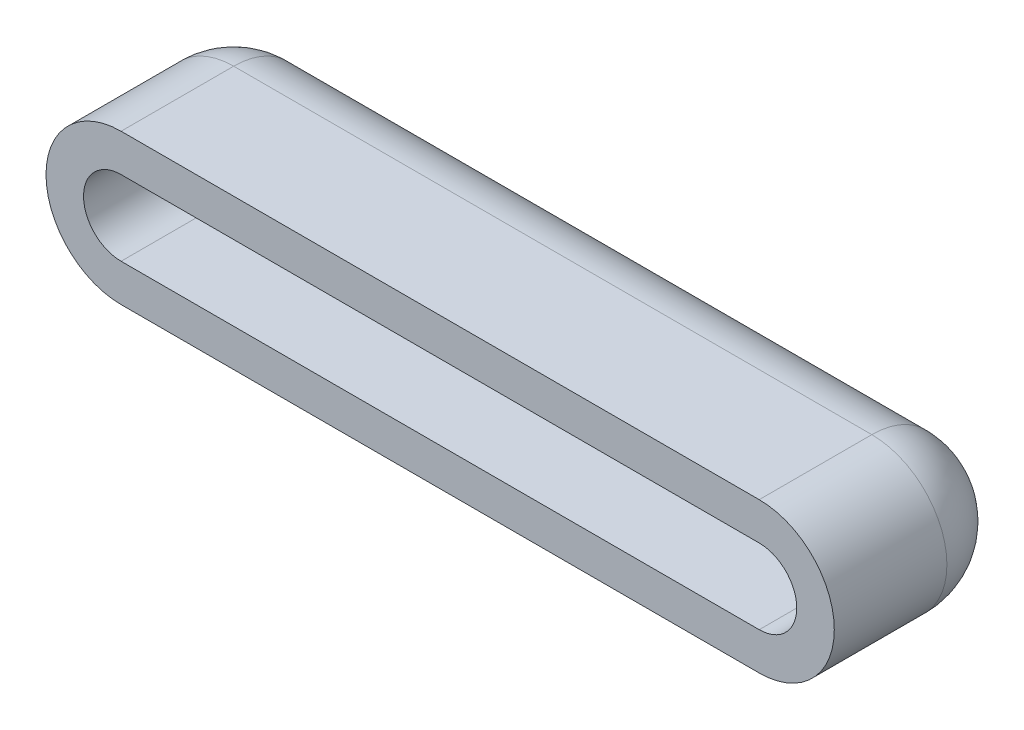
SolidWorks part; units mm, degrees
ref_plane "Plan de face" through (0, 0, 0) normal (0, 0, 1) x (1, 0, 0)
ref_plane "Plan de dessus" through (0, 0, 0) normal (0, 1, 0) x (1, 0, 0)
ref_plane "Plan de droite" through (0, 0, 0) normal (1, 0, 0) x (0, 0, -1)
sketch "Esquisse1" plane through (0, 0, 0) normal (0, 0, 1) x (1, 0, 0)
  line L0 (0, 0) -> (34, 0) construction
  line L1 (0, 4) -> (34, 4)
  line L2 (0, -4) -> (34, -4)
  arc A0 (0, 4) -> (0, -4) centre (0, 0) ccw
  arc A1 (34, -4) -> (34, 4) centre (34, 0) ccw
  point P3 (17, 0)
  dimension "D1" = 4
  dimension "D2" = 34
extrude "Boss.-Extru.1" add sketch "Esquisse1" along normal blind 10
shell "Coque1" thickness 2
fillet "Congé1" radius 4 4 edges at (17, 4, 0) (38, 0, 0) (17, -4, 0) (-4, 0, 0)
